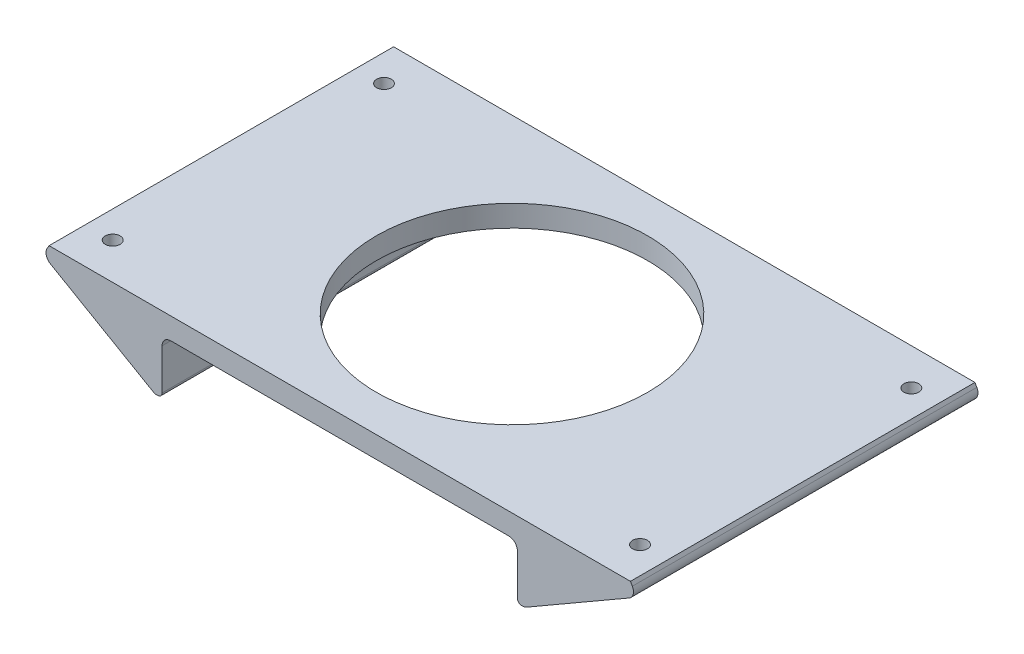
SolidWorks part; units mm, degrees
ref_plane "Front Plane" through (0, 0, 0) normal (0, 0, 1) x (1, 0, 0)
ref_plane "Top Plane" through (0, 0, 0) normal (0, 1, 0) x (1, 0, 0)
ref_plane "Right Plane" through (0, 0, 0) normal (1, 0, 0) x (0, 0, -1)
sketch "Sketch1" plane through (0, 0, 0) normal (0, 0, 1) x (1, 0, 0)
  line L0 (85.725, 0) -> (-85.725, 0)
  line L1 (-85.725, 0) -> (-87.5581, -3.175)
  line L2 (-87.5581, -3.175) -> (-54.5625, -22.225)
  line L3 (-54.5625, -22.225) -> (-52.3875, -22.225)
  line L4 (-52.3875, -22.225) -> (-52.3875, -6.35)
  line L5 (-52.3875, -6.35) -> (52.3875, -6.35)
  line L6 (0, 0) -> (0, -6.35) construction
  line L7 (52.3875, -22.225) -> (52.3875, -6.35)
  line L8 (54.5625, -22.225) -> (52.3875, -22.225)
  line L9 (87.5581, -3.175) -> (54.5625, -22.225)
  line L10 (85.725, 0) -> (87.5581, -3.175)
  point P14 (52.3875, -14.2875)
  dimension "D1" = 120
  dimension "D2" = 6.35
  dimension "D3" = 38.1
  dimension "D4" = 171.45
  dimension "D5" = 104.775
  dimension "D6" = 3.175
extrude "Boss-Extrude1" add sketch "Sketch1" along normal blind 101.6
sketch "Sketch2" plane through (0, 0, 0) normal (0, 1, 0) x (1, 0, 0)
  line L0 (0, -101.6) -> (0, 0) construction
  line L1 (85.725, -101.6) -> (-85.725, -101.6) construction
  line L2 (85.725, -50.8) -> (-85.725, -50.8) construction
  line L3 (85.725, -101.6) -> (85.725, 0) construction
  line L4 (-85.725, -101.6) -> (-85.725, 0) construction
  line L5 (52.3875, -101.6) -> (52.3875, 0) construction
  line L6 (52.3875, -101.6) -> (52.3875, 0) construction
  circle A0 centre (77.7558, -90.805) radius 2.1844
  circle A1 centre (-77.7557, -90.805) radius 2.1844
  circle A2 centre (-77.7557, -10.795) radius 2.1844
  circle A3 centre (77.7557, -10.795) radius 2.1844
  circle A4 centre (0, -50.8) radius 40.005
  point P20 (0, -90.805)
  point P22 (0, 0)
  dimension "D1" = 4.3688
  dimension "D2" = 155.5115
  dimension "D3" = 80.01
extrude "Cut-Extrude1" cut sketch "Sketch2" against normal through all
fillet "Fillet1" radius 2.54 4 edges at (-87.5581, -3.175, 50.8) (87.5581, -3.175, 50.8) (-52.3875, -6.35, 50.8) (52.3875, -6.35, 50.8)
fillet "Fillet2" radius 1.27 4 edges at (-54.5625, -22.225, 50.8) (-52.3875, -22.225, 50.8) (54.5625, -22.225, 50.8) (52.3875, -22.225, 50.8)
